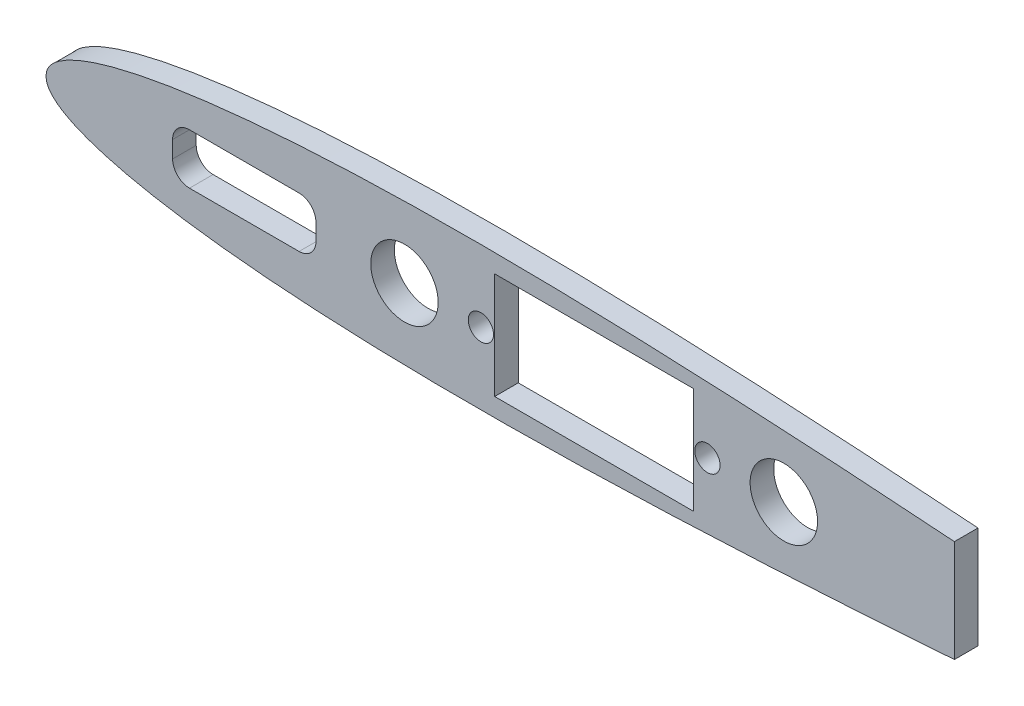
SolidWorks part; units mm, degrees
material "Фанера"
ref_plane "Front Plane" through (0, 0, 0) normal (0, 0, 1) x (1, 0, 0)
ref_plane "Top Plane" through (0, 0, 0) normal (0, 1, 0) x (1, 0, 0)
ref_plane "Right Plane" through (0, 0, 0) normal (1, 0, 0) x (0, 0, -1)
curve "Кривая1"
  spline degree 3 poles (110, 0, 0) (110.0276, -0.2367, 0) (110.0855, -0.7342, 0) (110.5302, -1.4271, 0) (111.1963, -2.0786, 0) (112.1098, -2.7013, 0) (113.2568, -3.2993, 0) (114.6379, -3.8731, 0) (116.2477, -4.4214, 0) (118.0813, -4.9426, 0) (120.1331, -5.4348, 0) (122.3972, -5.8961, 0) (124.8672, -6.3247, 0) (127.537, -6.7187, 0) (130.3997, -7.0764, 0) (133.4488, -7.3965, 0) (136.6771, -7.6776, 0) (140.0777, -7.9187, 0) (143.6433, -8.119, 0) (147.3662, -8.278, 0) (151.2389, -8.3955, 0) (155.2534, -8.4715, 0) (159.4016, -8.5065, 0) (163.6751, -8.501, 0) (168.0653, -8.456, 0) (172.5632, -8.3725, 0) (177.1595, -8.252, 0) (181.8446, -8.096, 0) (186.6087, -7.9062, 0) (191.4413, -7.6846, 0) (196.3316, -7.4331, 0) (201.2684, -7.1538, 0) (206.2396, -6.8489, 0) (211.233, -6.5205, 0) (216.2352, -6.1709, 0) (221.2323, -5.8022, 0) (226.2093, -5.417, 0) (231.1504, -5.0174, 0) (236.0382, -4.6058, 0) (240.8542, -4.1849, 0) (245.5777, -3.7574, 0) (250.1862, -3.3262, 0) (254.6542, -2.8948, 0) (258.9526, -2.4672, 0) (263.0477, -2.0479, 0) (266.899, -1.6426, 0) (270.4558, -1.2586, 0) (273.6512, -0.9053, 0) (276.3854, -0.5964, 0) (278.4526, -0.359, 0) (279.592, -0.2261, 0) (280, -0.1785, 0) knots 0 0 0 0 0.004099 0.008615 0.013935 0.020278 0.027753 0.03641 0.046266 0.05732 0.069559 0.082963 0.097507 0.113164 0.129903 0.14769 0.166492 0.186272 0.206992 0.228612 0.251092 0.274389 0.298458 0.323254 0.348728 0.37483 0.401509 0.42871 0.456376 0.484448 0.512864 0.541558 0.570462 0.599504 0.628607 0.65769 0.686667 0.715445 0.743924 0.771995 0.79954 0.826428 0.852512 0.877624 0.901571 0.924121 0.944989 0.963804 0.980044 0.992855 1 1 1 1
curve "Кривая2"
  spline degree 3 poles (280, 0.1785, 0) (279.592, 0.2261, 0) (278.4526, 0.359, 0) (276.3854, 0.5964, 0) (273.6512, 0.9053, 0) (270.4558, 1.2586, 0) (266.899, 1.6426, 0) (263.0477, 2.0479, 0) (258.9526, 2.4672, 0) (254.6542, 2.8948, 0) (250.1862, 3.3262, 0) (245.5777, 3.7574, 0) (240.8542, 4.1849, 0) (236.0382, 4.6058, 0) (231.1504, 5.0174, 0) (226.2093, 5.417, 0) (221.2323, 5.8022, 0) (216.2352, 6.1709, 0) (211.233, 6.5205, 0) (206.2396, 6.8489, 0) (201.2684, 7.1538, 0) (196.3316, 7.4331, 0) (191.4413, 7.6846, 0) (186.6087, 7.9062, 0) (181.8446, 8.096, 0) (177.1595, 8.252, 0) (172.5632, 8.3725, 0) (168.0653, 8.456, 0) (163.6751, 8.501, 0) (159.4016, 8.5065, 0) (155.2534, 8.4715, 0) (151.2389, 8.3955, 0) (147.3662, 8.278, 0) (143.6433, 8.119, 0) (140.0777, 7.9187, 0) (136.6771, 7.6776, 0) (133.4488, 7.3965, 0) (130.3997, 7.0764, 0) (127.537, 6.7187, 0) (124.8672, 6.3247, 0) (122.3972, 5.8961, 0) (120.1331, 5.4348, 0) (118.0813, 4.9426, 0) (116.2477, 4.4214, 0) (114.6379, 3.8731, 0) (113.2568, 3.2993, 0) (112.1098, 2.7013, 0) (111.1963, 2.0786, 0) (110.5302, 1.4271, 0) (110.0855, 0.7342, 0) (110.0276, 0.2367, 0) (110, 0, 0) knots 0 0 0 0 0.007145 0.019956 0.036196 0.055011 0.075879 0.098429 0.122376 0.147488 0.173572 0.20046 0.228005 0.256076 0.284555 0.313333 0.34231 0.371393 0.400496 0.429538 0.458442 0.487136 0.515552 0.543624 0.57129 0.598491 0.62517 0.651272 0.676746 0.701542 0.725611 0.748908 0.771388 0.793008 0.813728 0.833508 0.85231 0.870097 0.886836 0.902493 0.917037 0.930441 0.94268 0.953734 0.96359 0.972247 0.979722 0.986065 0.991385 0.995901 1 1 1 1
sketch "Эскиз1" plane through (0, 0, 0) normal (0, 0, 1) x (1, 0, 0)
  line L0 (105.1708, 0) -> (280.7263, 0) construction
  line L1 (280.0739, 0) -> (280.0739, 24.3846) construction
  line L2 (110, -5.3315) -> (110, 17.5304) construction
  line L3 (152.5185, 18.8331) -> (152.5185, -21.3473) construction
  line L4 (223.3826, 13.2402) -> (223.3826, -18.4275) construction
  line L5 (217.7476, 6.0581) -> (217.7476, -6.0581)
  line L6 (127.0185, -3) -> (140.0185, -3)
  line L7 (125.0185, -1) -> (125.0185, 1)
  line L8 (127.0185, 3) -> (140.0185, 3)
  line L9 (142.0185, -1) -> (142.0185, 1)
  line L10 (125.0185, -3) -> (142.0185, 3) construction
  line L11 (125.0185, 3) -> (142.0185, -3) construction
  line L16 (175.0185, 15.5451) -> (175.0185, -13.0112) construction
  line L17 (163.2185, -6.3) -> (186.8185, -6.3)
  line L18 (163.2185, -6.3) -> (163.2185, 6.3)
  line L19 (163.2185, 6.3) -> (186.8185, 6.3)
  line L20 (186.8185, -6.3) -> (186.8185, 6.3)
  line L21 (163.2185, -6.3) -> (186.8185, 6.3) construction
  line L22 (163.2185, 6.3) -> (186.8185, -6.3) construction
  line L23 (186.8185, 6.3) -> (190.0885, 6.3) construction
  line L24 (190.0885, 6.3) -> (190.0885, -6.3) construction
  line L25 (190.0885, -6.3) -> (186.8185, -6.3) construction
  arc A0 (280, 0.1785) -> (280, -0.1785) centre (279.8215, 0) cw
  circle A1 centre (152.5185, 0) radius 4
  circle A2 centre (197.5185, 0) radius 4
  arc A7 (125.0185, 1) -> (127.0185, 3) centre (127.0185, 1) cw
  arc A8 (127.0185, -3) -> (125.0185, -1) centre (127.0185, -1) cw
  arc A9 (140.0185, -3) -> (142.0185, -1) centre (140.0185, -1) ccw
  arc A10 (140.0185, 3) -> (142.0185, 1) centre (140.0185, 1) cw
  arc A11 (223.3826, 5.635) -> (223.3826, -5.635) centre (223.3826, 0) ccw
  circle A12 centre (223.3826, 0) radius 1
  circle A13 centre (188.4535, 0) radius 1.5
  circle A14 centre (161.5835, 0) radius 1.5
  spline S0 degree 3 poles (-4661.4324, -1487.7365) (211.2329, 54.6037) (104.074, 8.632) (110.5302, -1.4271) (111.1963, -2.0786) (112.1098, -2.7013) (113.2568, -3.2993) (114.6379, -3.8731) (116.2477, -4.4214) (118.0813, -4.9426) (120.1331, -5.4348) (122.3972, -5.8961) (124.8672, -6.3247) (127.537, -6.7187) (130.3997, -7.0764) (133.4488, -7.3965) (136.6771, -7.6776) (140.0777, -7.9187) (143.6433, -8.119) (147.3662, -8.278) (151.2389, -8.3955) (155.2534, -8.4715) (159.4016, -8.5065) (163.6751, -8.501) (168.0653, -8.456) (172.5632, -8.3725) (177.1595, -8.252) (181.8446, -8.096) (186.6087, -7.9062) (191.4413, -7.6846) (196.3316, -7.4331) (201.2684, -7.1538) (206.2396, -6.8489) (211.233, -6.5205) (216.2352, -6.1709) (221.2323, -5.8022) (226.2093, -5.417) (231.1504, -5.0174) (236.0382, -4.6058) (240.8542, -4.1849) (247.0711, -3.6222) (253.1161, -3.0479) (258.9526, -2.4672) (263.0477, -2.0479) (266.899, -1.6426) (270.4558, -1.2586) (273.6512, -0.9053) (276.3854, -0.5964) (388.7024, 12.3066) (497.9224, 43.7854) (1184.9183, -4906.7149) knots -0.18838 -0.18838 -0.18838 -0.18838 0.004099 0.008615 0.013935 0.020278 0.027753 0.03641 0.046266 0.05732 0.069559 0.082963 0.097507 0.113164 0.129903 0.14769 0.166492 0.186272 0.206992 0.228612 0.251092 0.274389 0.298458 0.323254 0.348728 0.37483 0.401509 0.42871 0.456376 0.484448 0.512864 0.541558 0.570462 0.599504 0.628607 0.65769 0.686667 0.715445 0.743924 0.771995 0.79954 0.852512 0.877624 0.901571 0.924121 0.944989 0.963804 0.980044 0.992855 2.930469 2.930469 2.930469 2.930469 only from (110, 0) to (280, -0.1785) construction
  spline S1 degree 3 poles (1184.9123, 4906.671) (497.9217, -43.7853) (388.702, -12.3066) (276.3854, 0.5964) (273.6512, 0.9053) (270.4558, 1.2586) (266.899, 1.6426) (263.0477, 2.0479) (258.9526, 2.4672) (253.1161, 3.0479) (247.0711, 3.6222) (240.8542, 4.1849) (236.0382, 4.6058) (231.1504, 5.0174) (226.2093, 5.417) (221.2323, 5.8022) (216.2352, 6.1709) (211.233, 6.5205) (206.2396, 6.8489) (201.2684, 7.1538) (196.3316, 7.4331) (191.4413, 7.6846) (186.6087, 7.9062) (181.8446, 8.096) (177.1595, 8.252) (172.5632, 8.3725) (168.0653, 8.456) (163.6751, 8.501) (159.4016, 8.5065) (155.2534, 8.4715) (151.2389, 8.3955) (147.3662, 8.278) (143.6433, 8.119) (140.0777, 7.9187) (136.6771, 7.6776) (133.4488, 7.3965) (130.3997, 7.0764) (127.537, 6.7187) (124.8672, 6.3247) (122.3972, 5.8961) (120.1331, 5.4348) (118.0813, 4.9426) (116.2477, 4.4214) (114.6379, 3.8731) (113.2568, 3.2993) (112.1098, 2.7013) (111.1963, 2.0786) (110.5302, 1.4271) (104.0737, -8.6325) (211.2431, -54.6081) (-4662.1426, 1487.9613) knots -1.930463 -1.930463 -1.930463 -1.930463 0.007145 0.019956 0.036196 0.055011 0.075879 0.098429 0.122376 0.147488 0.20046 0.228005 0.256076 0.284555 0.313333 0.34231 0.371393 0.400496 0.429538 0.458442 0.487136 0.515552 0.543624 0.57129 0.598491 0.62517 0.651272 0.676746 0.701542 0.725611 0.748908 0.771388 0.793008 0.813728 0.833508 0.85231 0.870097 0.886836 0.902493 0.917037 0.930441 0.94268 0.953734 0.96359 0.972247 0.979722 0.986065 0.991385 0.995901 1.188389 1.188389 1.188389 1.188389 only from (280, 0.1785) to (110, 0) construction
  spline S2 degree 3 poles (110, 0) (110.0276, -0.2367) (110.0855, -0.7342) (110.5302, -1.4271) (111.1963, -2.0786) (112.1098, -2.7013) (113.2568, -3.2993) (114.6379, -3.8731) (116.2477, -4.4214) (118.0813, -4.9426) (120.1331, -5.4348) (122.3972, -5.8961) (124.8672, -6.3247) (127.537, -6.7187) (130.3997, -7.0764) (133.4488, -7.3965) (136.6771, -7.6776) (140.0777, -7.9187) (143.6433, -8.119) (147.3662, -8.278) (151.2389, -8.3955) (155.2534, -8.4715) (159.4016, -8.5065) (163.6751, -8.501) (168.0653, -8.456) (172.5632, -8.3725) (177.1595, -8.252) (181.8446, -8.096) (186.6087, -7.9062) (191.4413, -7.6846) (196.3316, -7.4331) (201.2684, -7.1538) (206.2396, -6.8489) (211.233, -6.5205) (216.2352, -6.1709) (221.2323, -5.8022) (226.2093, -5.417) (231.1504, -5.0174) (236.0382, -4.6058) (240.8542, -4.1849) (247.0711, -3.6222) (253.1161, -3.0479) (258.9526, -2.4672) (263.0477, -2.0479) (266.899, -1.6426) (270.4558, -1.2586) (273.6512, -0.9053) (276.3854, -0.5964) (278.4526, -0.359) (279.592, -0.2261) (280, -0.1785) knots 0 0 0 0 0.004099 0.008615 0.013935 0.020278 0.027753 0.03641 0.046266 0.05732 0.069559 0.082963 0.097507 0.113164 0.129903 0.14769 0.166492 0.186272 0.206992 0.228612 0.251092 0.274389 0.298458 0.323254 0.348728 0.37483 0.401509 0.42871 0.456376 0.484448 0.512864 0.541558 0.570462 0.599504 0.628607 0.65769 0.686667 0.715445 0.743924 0.771995 0.79954 0.852512 0.877624 0.901571 0.924121 0.944989 0.963804 0.980044 0.992855 1 1 1 1
  spline S3 degree 3 poles (280, 0.1785) (279.592, 0.2261) (278.4526, 0.359) (276.3854, 0.5964) (273.6512, 0.9053) (270.4558, 1.2586) (266.899, 1.6426) (263.0477, 2.0479) (258.9526, 2.4672) (253.1161, 3.0479) (247.0711, 3.6222) (240.8542, 4.1849) (236.0382, 4.6058) (231.1504, 5.0174) (226.2093, 5.417) (221.2323, 5.8022) (216.2352, 6.1709) (211.233, 6.5205) (206.2396, 6.8489) (201.2684, 7.1538) (196.3316, 7.4331) (191.4413, 7.6846) (186.6087, 7.9062) (181.8446, 8.096) (177.1595, 8.252) (172.5632, 8.3725) (168.0653, 8.456) (163.6751, 8.501) (159.4016, 8.5065) (155.2534, 8.4715) (151.2389, 8.3955) (147.3662, 8.278) (143.6433, 8.119) (140.0777, 7.9187) (136.6771, 7.6776) (133.4488, 7.3965) (130.3997, 7.0764) (127.537, 6.7187) (124.8672, 6.3247) (122.3972, 5.8961) (120.1331, 5.4348) (118.0813, 4.9426) (116.2477, 4.4214) (114.6379, 3.8731) (113.2568, 3.2993) (112.1098, 2.7013) (111.1963, 2.0786) (110.5302, 1.4271) (110.0855, 0.7342) (110.0276, 0.2367) (110, 0) knots 0 0 0 0 0.007145 0.019956 0.036196 0.055011 0.075879 0.098429 0.122376 0.147488 0.20046 0.228005 0.256076 0.284555 0.313333 0.34231 0.371393 0.400496 0.429538 0.458442 0.487136 0.515552 0.543624 0.57129 0.598491 0.62517 0.651272 0.676746 0.701542 0.725611 0.748908 0.771388 0.793008 0.813728 0.833508 0.85231 0.870097 0.886836 0.902493 0.917037 0.930441 0.94268 0.953734 0.96359 0.972247 0.979722 0.986065 0.991385 0.995901 1 1 1 1
  point P19 (175.0185, 0)
  point P22 (133.5185, 0)
  point P31 (223.3826, -5.635)
  point P37 (188.4535, 6.3)
  point P54 (223.3826, 5.635)
  point P55 (223.3826, -5.635)
  point P56 (223.3826, 5.635)
  dimension "D1" = 0.2524
  dimension "D3" = 8
  dimension "D14" = 5.635
  dimension "D15" = 2
  dimension "D10" = 2
  dimension "D16" = 3
  dimension "D2" = 170.0739
  dimension "D4" = 42.5185
  dimension "D5" = 56.6913
  dimension "D6" = 45
  dimension "D7" = 6
  dimension "D8" = 17
  dimension "D9" = 19
  dimension "D11" = 12.6
  dimension "D12" = 23.6
  dimension "D13" = 22.5
  dimension "D17" = 3.27
extrude "Бобышка-Вытянуть1" add sketch "Эскиз1" along normal mid plane 2.8
equation "\"D4@Эскиз1\"=\"D2@Эскиз1\"/4"
equation "\"D5@Эскиз1\"=\"D2@Эскиз1\"/3"
equation "\"D13@Эскиз1\"=\"D6@Эскиз1\"/2"
